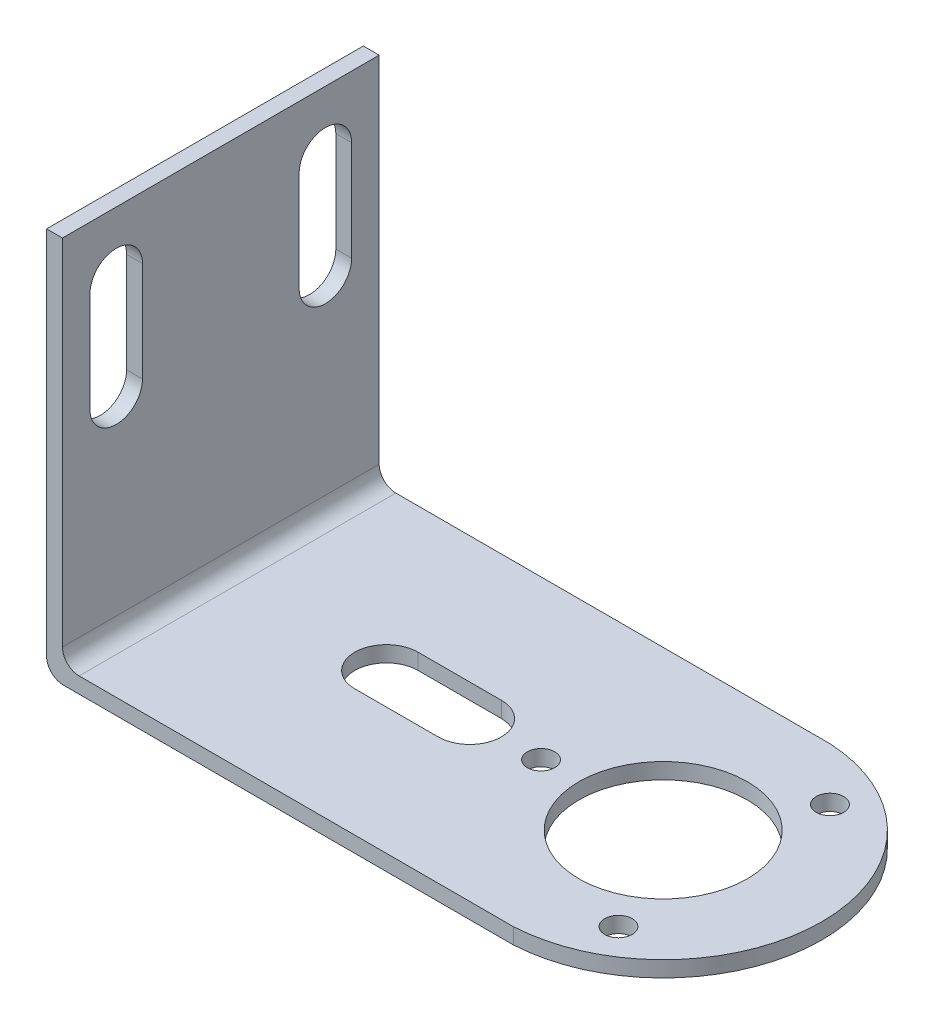
SolidWorks part; units mm, degrees
ref_plane "Front Plane" through (0, 0, 0) normal (0, 0, 1) x (1, 0, 0)
ref_plane "Top Plane" through (0, 0, 0) normal (0, 1, 0) x (1, 0, 0)
ref_plane "Right Plane" through (0, 0, 0) normal (1, 0, 0) x (0, 0, -1)
sketch "Sketch1" plane through (0, 0, 0) normal (0, 1, 0) x (1, 0, 0)
  line L0 (19, 19) -> (19, -19) construction
  line L1 (-37, -19) -> (37, -19)
  line L2 (-37, -19) -> (-37, 19)
  line L3 (-37, 19) -> (37, 19)
  line L4 (37, -19) -> (37, 19)
  line L5 (-37, -19) -> (37, 19) construction
  line L6 (-37, 19) -> (37, -19) construction
  line L7 (-15.2278, 0) -> (-5.2278, 0) construction
  line L8 (-15.2278, 3.8) -> (-5.2278, 3.8)
  line L9 (-15.2278, -3.8) -> (-5.2278, -3.8)
  line L10 (0, 0) -> (0, -1.0324)
  line L11 (0, 0) -> (51.1821, 0) construction
  arc A0 (19, -19) -> (19, 19) centre (17.9722, 0) ccw
  circle A1 centre (17.9722, 0) radius 10.1
  circle A2 centre (3.3222, 0) radius 1.65
  arc A3 (-15.2278, 3.8) -> (-15.2278, -3.8) centre (-15.2278, 0) ccw
  arc A4 (-5.2278, -3.8) -> (-5.2278, 3.8) centre (-5.2278, 0) ccw
  circle A5 centre (25.2972, 12.6873) radius 1.65
  circle A6 centre (25.2972, -12.6873) radius 1.65
  point P0 (0, 0)
  point P11 (-10.2278, 0)
  point P19 (17.9722, 0)
  point P29 (17.9722, 0)
  dimension "D4" = 20.2
  dimension "D5" = 3.3
  dimension "D9" = 3.8
  dimension "D12" = 3
  dimension "D1" = 38
  dimension "D2" = 74
  dimension "D3" = 56
  dimension "D6" = 14.65
  dimension "D7" = 7.6
  dimension "D8" = 15.2
  dimension "D10" = 10
  dimension "D11" = 8.55
extrude "Boss-Extrude1" add sketch "Sketch1" along normal blind 1.9
sketch "Sketch2" plane through (0, 1.9, 0) normal (0, 1, 0) x (1, 0, 0)
  line L0 (-37, -19) -> (19, -19) construction
  line L1 (-37, 19) -> (-35.1, 19)
  line L2 (-37, 19) -> (-37, -19)
  line L3 (-37, -19) -> (-35.1, -19)
  line L4 (-35.1, 19) -> (-35.1, -19)
  dimension "D1" = 1.9
extrude "Boss-Extrude2" add sketch "Sketch2" along normal blind 44.5
sketch "Sketch3" plane through (-35.1, 0, 0) normal (1, 0, 0) x (0, 0, -1)
  line L0 (0, 46.4) -> (0, 50.0346) construction
  line L2 (-19, 46.4) -> (-19, 1.9) construction
  line L3 (-15.7, 26.95) -> (-9.4, 26.95)
  line L4 (-15.7, 26.95) -> (-15.7, 38.95)
  line L6 (-15.7, 38.95) -> (-9.4, 38.95)
  line L7 (-9.4, 26.95) -> (-9.4, 38.95)
  line L8 (-15.7, 26.95) -> (-9.4, 38.95) construction
  line L9 (-15.7, 38.95) -> (-9.4, 26.95) construction
  line L11 (-19, 46.4) -> (19, 46.4) construction
  line L12 (15.7, 38.95) -> (9.4, 26.95) construction
  line L13 (15.7, 26.95) -> (9.4, 38.95) construction
  line L14 (9.4, 26.95) -> (9.4, 38.95)
  line L15 (15.7, 38.95) -> (9.4, 38.95)
  line L16 (15.7, 26.95) -> (15.7, 38.95)
  line L17 (15.7, 26.95) -> (9.4, 26.95)
  circle A0 centre (-12.55, 38.95) radius 3.15
  circle A1 centre (-12.55, 26.95) radius 3.15
  circle A2 centre (12.55, 26.95) radius 3.15
  circle A3 centre (12.55, 38.95) radius 3.15
  point P1 (-12.55, 32.95)
  point P24 (12.55, 32.95)
  dimension "D4" = 7.45
  dimension "D5" = 6.3
  dimension "D1" = 3.3
  dimension "D2" = 6.3
  dimension "D3" = 12
extrude "Cut-Extrude1" cut sketch "Sketch3" against normal up to next contours L6 A0 | L6 A0 | A1 L7 A0 L4 | L3 A1 | L16 A3 L14 A2 | A3 L15 | A3 L15 | A2 L17 | A2 L17 | L3 A1
fillet "Fillet1" radius 2 2 edges at (-37, 0, 0) (-35.1, 1.9, 0)
